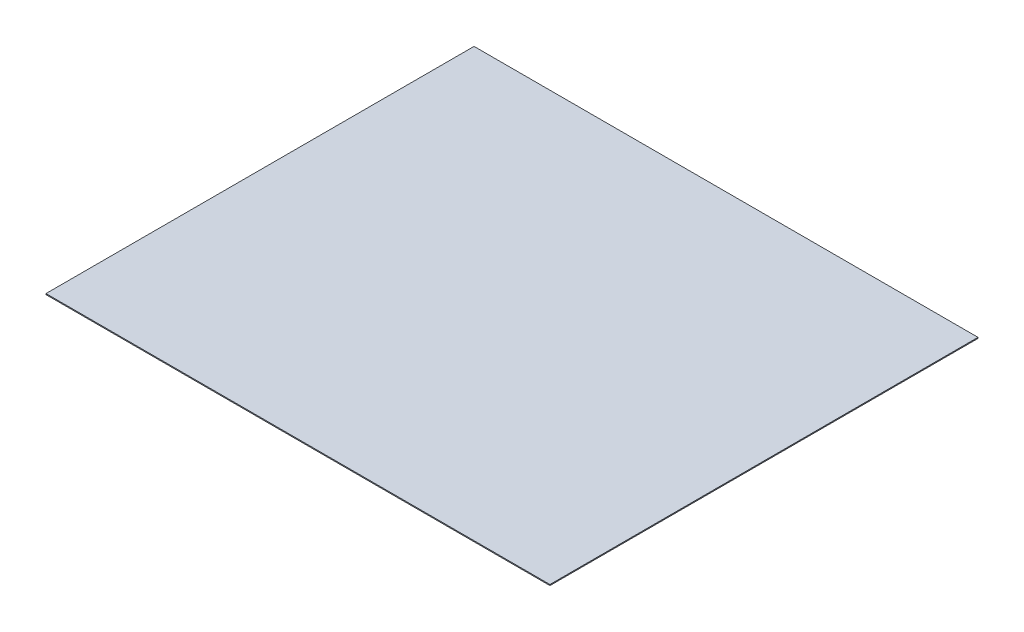
SolidWorks part; units mm, degrees
ref_plane "Alzado" through (0, 0, 0) normal (0, 0, 1) x (1, 0, 0)
ref_plane "Planta" through (0, 0, 0) normal (0, 1, 0) x (1, 0, 0)
ref_plane "Vista lateral" through (0, 0, 0) normal (1, 0, 0) x (0, 0, -1)
sketch "Croquis1" plane through (0, 0, 0) normal (0, 1, 0) x (1, 0, 0)
  line L1 (0, 0) -> (1481.2, 0)
  line L2 (0, 0) -> (0, -1258.2)
  line L3 (0, -1258.2) -> (1481.2, -1258.2)
  line L4 (1481.2, 0) -> (1481.2, -1258.2)
  dimension "D1" = 1258.2
  dimension "D2" = 1481.2
extrude "Saliente-Extruir1" add sketch "Croquis1" along normal blind 2.9
